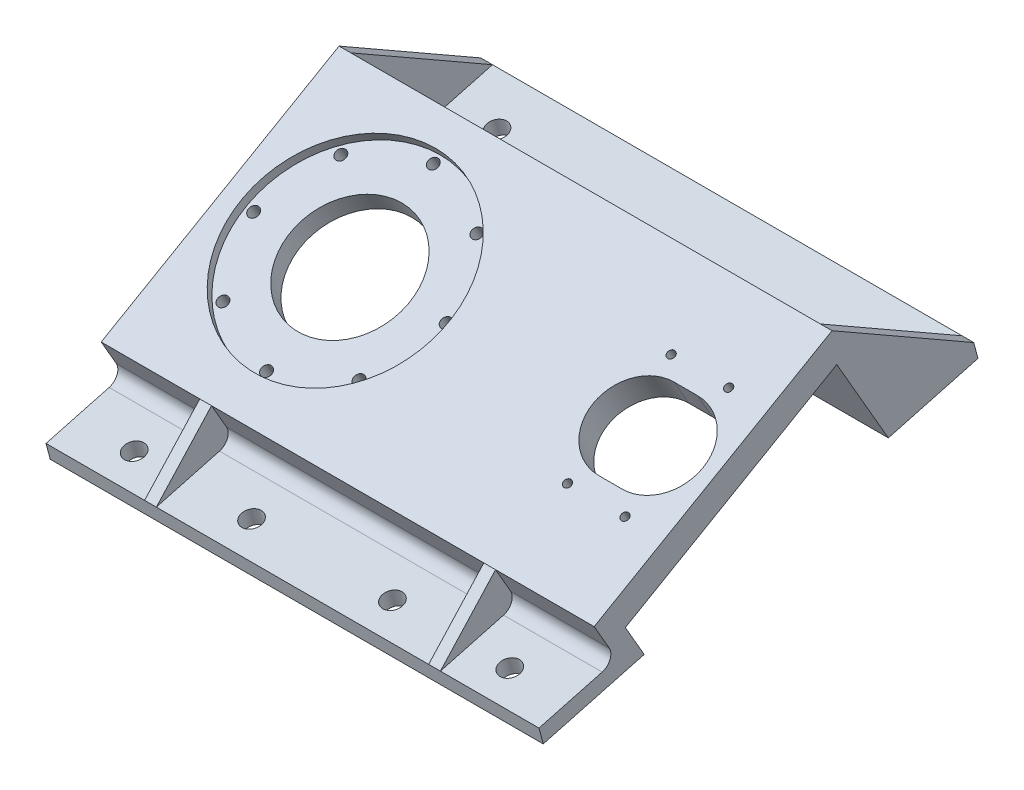
SolidWorks part; units mm, degrees
other "标注1"
sketch "草图25" plane through (-52, 30, -95) normal (-0.4172, 0.7166, -0.559) x (-0.8994, -0.2372, 0.3671)
other "标注2"
sketch "草图26" plane through (-52, 30, -95) normal (-0.4172, 0.7166, -0.559) x (-0.8994, -0.2372, 0.3671)
material "1060 合金"
ref_plane "前视基准面" through (0, 0, 0) normal (0, 0, 1) x (1, 0, 0)
ref_plane "上视基准面" through (0, 0, 0) normal (0, 1, 0) x (1, 0, 0)
ref_plane "右视基准面" through (0, 0, 0) normal (1, 0, 0) x (0, 0, -1)
sketch "草图1" plane through (0, 0, 0) normal (0, 1, 0) x (1, 0, 0)
  line L0 (0, 0) -> (170, 0) construction
  line L1 (170, 31.93) -> (170, -31.93)
  line L2 (15.8391, 73.3084) -> (162.1119, 41.7045)
  line L3 (15.8391, -73.3084) -> (162.1119, -41.7045)
  arc A0 (15.8391, 73.3084) -> (15.8391, -73.3084) centre (0, 0) ccw
  arc A1 (162.1119, -41.7045) -> (170, -31.93) centre (160, -31.93) ccw
  arc A2 (170, 31.93) -> (162.1119, 41.7045) centre (160, 31.93) ccw
  point P6 (170, 0)
  dimension "D1" = 150
  dimension "D4" = 20
  dimension "D5" = 20
  dimension "D2" = 170
  dimension "D3" = 63.86
extrude "凸台-拉伸1" add sketch "草图1" along normal blind 30
sketch "草图2" plane through (0, 30, 0) normal (0, 1, 0) x (1, 0, 0)
  circle A0 centre (0, 0) radius 44.45
  dimension "D1" = 88.9
extrude "切除-拉伸1" cut sketch "草图2" against normal blind 4
sketch "草图3" plane through (0, 26, 0) normal (0, 1, 0) x (1, 0, 0)
  line L0 (0, 0) -> (0, 90.3276) construction
  circle A0 centre (0, 0) radius 25.5
  circle A1 centre (0, 41) radius 2.25
  circle A2 centre (28.9914, 28.9914) radius 2.25
  circle A3 centre (41, 0) radius 2.25
  circle A4 centre (28.9914, -28.9914) radius 2.25
  circle A5 centre (0, -41) radius 2.25
  circle A6 centre (-28.9914, -28.9914) radius 2.25
  circle A7 centre (-41, 0) radius 2.25
  circle A8 centre (-28.9914, 28.9914) radius 2.25
  dimension "D1" = 51
  dimension "D3" = 4.5
  dimension "D2" = 41
  dimension "D4" = 8
extrude "切除-拉伸2" cut sketch "草图3" against normal through all contours A2 | A3 | A4 | A5 | A6 | A7 | A8 | A1 | A0
sketch "草图4" plane through (0, 30, 0) normal (0, 1, 0) x (1, 0, 0)
  line L0 (0, 0) -> (134, 0) construction
  line L1 (124, 18.5) -> (134, 18.5)
  line L2 (124, -18.5) -> (134, -18.5)
  arc A0 (134, -18.5) -> (134, 18.5) centre (134, 0) ccw
  arc A1 (124, 18.5) -> (124, -18.5) centre (124, 0) ccw
  dimension "D2" = 37
  dimension "D3" = 37
  dimension "D1" = 134
  dimension "D4" = 10
extrude "切除-拉伸3" cut sketch "草图4" against normal through all
sketch "草图5" plane through (0, 30, 0) normal (0, 1, 0) x (1, 0, 0)
  arc A0 (134, -18.5) -> (134, 18.5) centre (134, 0) ccw construction
  arc A1 (124, 18.5) -> (124, -18.5) centre (124, 0) ccw construction
  arc A2 (134, -18.5) -> (134, 18.5) centre (134, 0) ccw construction
  arc A3 (124, 18.5) -> (124, -18.5) centre (124, 0) ccw construction
  circle A4 centre (116.75, 25.5) radius 1.65
  circle A5 centre (141.25, 25.5) radius 1.65
  circle A6 centre (141.25, -25.5) radius 1.65
  circle A7 centre (116.75, -25.5) radius 1.65
  dimension "D1" = 3.3
  dimension "D2" = 3.3
  dimension "D3" = 3.3
  dimension "D4" = 3.3
  dimension "D7" = 25.5
  dimension "D5" = 7.25
  dimension "D6" = 25.5
  dimension "D8" = 7.25
  dimension "D9" = 7.25
extrude "切除-拉伸4" cut sketch "草图5" against normal through all
sketch "草图6" plane through (0, 30, 0) normal (0, 1, 0) x (1, 0, 0)
  line L0 (158, 42.5929) -> (158, -42.5929) construction
  line L2 (-52, 54.0463) -> (-52, -54.0463) construction
  line L6 (162.1119, 41.7045) -> (15.8391, 73.3084) construction
  line L7 (15.8391, -73.3084) -> (162.1119, -41.7045) construction
  line L8 (-52, 95) -> (-52, -95)
  line L9 (158, 95) -> (158, -95)
  line L10 (-52, 95) -> (158, 95)
  line L11 (-52, -95) -> (158, -95)
  line L15 (162.1119, 41.7045) -> (15.8391, 73.3084)
  line L16 (15.8391, -73.3084) -> (162.1119, -41.7045)
  line L17 (170, -31.93) -> (170, 31.93)
  line L18 (162.1119, 41.7045) -> (15.8391, 73.3084)
  line L19 (15.8391, -73.3084) -> (162.1119, -41.7045)
  line L20 (170, -31.93) -> (170, 31.93)
  arc A0 (15.8391, 73.3084) -> (15.8391, -73.3084) centre (0, 0) ccw construction
  arc A6 (170, 31.93) -> (162.1119, 41.7045) centre (160, 31.93) ccw
  arc A7 (15.8391, 73.3084) -> (15.8391, -73.3084) centre (0, 0) ccw
  arc A8 (162.1119, -41.7045) -> (170, -31.93) centre (160, -31.93) ccw
  arc A9 (170, 31.93) -> (162.1119, 41.7045) centre (160, 31.93) ccw
  arc A10 (15.8391, 73.3084) -> (15.8391, -73.3084) centre (0, 0) ccw
  arc A11 (162.1119, -41.7045) -> (170, -31.93) centre (160, -31.93) ccw
  point P8 (-52, 0)
  point P13 (158, 0)
  line M26 (162.1119, 41.7045) -> (15.8391, 73.3084)
  arc M27 (15.8391, 73.3084) -> (15.8391, -73.3084) centre (0, 0) ccw
  line M28 (15.8391, -73.3084) -> (162.1119, -41.7045)
  dimension "D3" = 190
  dimension "D1" = 210
  dimension "D2" = 52
  dimension "D4" = 190
  dimension "D5" = 0
extrude "凸台-拉伸2" add sketch "草图6" against normal blind 30 contours L10 L8 L9 M27 M26 | L8 L11 L9 M28 M27
sketch "草图7" plane through (0, 30, 0) normal (0, 1, 0) x (1, 0, 0)
  line L0 (-52, 54.0463) -> (-52, -54.0463)
  line L1 (158, 42.5929) -> (158, -42.5929)
  line L9 (162.1119, 41.7045) -> (158, 42.5929)
  line L10 (158, 42.5929) -> (158, 95)
  line L11 (158, 95) -> (-52, 95)
  line L12 (-52, 95) -> (-52, 54.0463)
  line L13 (-52, -54.0463) -> (-52, -95)
  line L14 (-52, -95) -> (158, -95)
  line L15 (158, -95) -> (158, -42.5929)
  line L16 (158, -42.5929) -> (162.1119, -41.7045)
  line L17 (170, -31.93) -> (170, 31.93)
  line L18 (162.1119, 41.7045) -> (158, 42.5929)
  line L21 (-52, 95) -> (-52, 54.0463)
  line L25 (158, -42.5929) -> (162.1119, -41.7045)
  line L26 (170, -31.93) -> (170, 31.93)
  arc A3 (170, 31.93) -> (162.1119, 41.7045) centre (160, 31.93) ccw
  arc A4 (-52, 54.0463) -> (-52, -54.0463) centre (0, 0) ccw
  arc A5 (162.1119, -41.7045) -> (170, -31.93) centre (160, -31.93) ccw
  arc A6 (170, 31.93) -> (162.1119, 41.7045) centre (160, 31.93) ccw
  arc A7 (-52, 54.0463) -> (-52, -54.0463) centre (0, 0) ccw
  arc A8 (162.1119, -41.7045) -> (170, -31.93) centre (160, -31.93) ccw
  arc M22 (170, 31.93) -> (162.1119, 41.7045) centre (160, 31.93) ccw
  line M23 (162.1119, 41.7045) -> (158, 42.5929)
  arc M27 (-52, 54.0463) -> (-52, -54.0463) centre (0, 0) ccw
  line M31 (158, -42.5929) -> (162.1119, -41.7045)
  arc M32 (162.1119, -41.7045) -> (170, -31.93) centre (160, -31.93) ccw
  line M33 (170, -31.93) -> (170, 31.93)
  dimension "D1" = 0
extrude "切除-拉伸5" cut sketch "草图7" against normal through all contours L0 M27 | L1 M23 M31 M32 M33 M22
sketch "草图9" plane through (-52, 0, 0) normal (-1, 0, 0) x (0, 0, 1)
  line L0 (-95, 20) -> (-60, 10.6218)
  line L1 (-95, 30) -> (95, 30) construction
  line L3 (-60, 10.6218) -> (-60, 30)
  line L5 (-95, 0) -> (-95, 30) construction
  line L7 (-95, 20) -> (-95, 30)
  line L8 (-95, 30) -> (-60, 30)
  dimension "D1" = 15
  dimension "D3" = 19.3782
  dimension "D4" = 35
  dimension "D5" = 10
extrude "切除-拉伸7" cut sketch "草图9" against normal through all contours L8 L3 L0 L7
sketch "草图8" plane through (-52, 0, 0) normal (-1, 0, 0) x (0, 0, 1)
  line L0 (0, 0) -> (52, 0)
  line L1 (-95, 0) -> (95, 0) construction
  line L2 (52, 0) -> (52, 17.3)
  line L3 (52, 17.3) -> (-52, 17.3)
  line L4 (-52, 17.3) -> (-52, 0)
  line L5 (-52, 0) -> (0, 0)
  line L6 (-60, 30) -> (95, 30) construction
  dimension "D1" = 52
  dimension "D2" = 52
  dimension "D3" = 12.7
sketch "草图10" plane through (-52, 0, 0) normal (-1, 0, 0) x (0, 0, 1)
  line L0 (-95, 12.7531) -> (-47.4049, 0) construction
  line L1 (-95, 0) -> (-95, 20) construction
  line L2 (-95, 0) -> (95, 0) construction
  line L3 (-95, 20) -> (-60, 10.6218) construction
  line L6 (-95, 12.7531) -> (-52, 1.2313)
  line L7 (-52, 1.2313) -> (-52, 0)
  line L8 (-95, 12.7531) -> (-95, 0)
  line L9 (-95, 0) -> (-52, 0)
  line L10 (-52, 17.3) -> (-52, 0) construction
  dimension "D1" = 7
extrude "切除-拉伸8" cut sketch "草图10" against normal through all
extrude "切除-拉伸9" cut sketch "草图8" against normal through all
fillet "圆角1" radius 5 1 edges at (53, 10.6218, -60)
sketch "草图11" plane through (-52, 0, 0) normal (-1, 0, 0) x (0, 0, 1)
  line L0 (-95, 12.7531) -> (-93.1883, 19.5145)
  line L1 (-95, 20) -> (-66.2941, 12.3083) construction
  line L2 (-93.1883, 19.5145) -> (-95, 20)
  line L3 (-95, 20) -> (-95, 12.7531)
extrude "切除-拉伸10" cut sketch "草图11" against normal through all
sketch "草图12" plane through (-52, 0, 0) normal (-1, 0, 0) x (0, 0, 1)
  line L0 (-93.1883, 19.5145) -> (-60, 30)
  line L10 (-93.1883, 19.5145) -> (-95, 12.7531)
  line L11 (-95, 12.7531) -> (-52, 1.2313)
  line L12 (-52, 1.2313) -> (-52, 17.3)
  line L13 (-52, 17.3) -> (52, 17.3)
  line L14 (52, 17.3) -> (52, 0)
  line L15 (52, 0) -> (95, 0)
  line L16 (95, 0) -> (95, 30)
  line L17 (95, 30) -> (-60, 30)
  line L18 (-60, 30) -> (-60, 17.1379)
  line L19 (-66.2941, 12.3083) -> (-93.1883, 19.5145)
  line L28 (-60, 30) -> (-60, 17.1379)
  line L29 (-66.2941, 12.3083) -> (-93.1883, 19.5145)
  arc A1 (-66.2941, 12.3083) -> (-60, 17.1379) centre (-65, 17.1379) ccw
  arc A2 (-66.2941, 12.3083) -> (-60, 17.1379) centre (-65, 17.1379) ccw
  dimension "D1" = 0
extrude "凸台-拉伸3" add sketch "草图12" against normal blind 5
sketch "草图13" plane through (158, 0, 0) normal (1, 0, 0) x (0, 0, -1)
  line L3 (66.2941, 12.3083) -> (93.1883, 19.5145)
  line L4 (93.1883, 19.5145) -> (60, 30)
  line L5 (60, 30) -> (60, 17.1379)
  line L6 (66.2941, 12.3083) -> (93.1883, 19.5145)
  line L7 (93.1883, 19.5145) -> (60, 30)
  line L8 (60, 30) -> (60, 17.1379)
  arc A1 (60, 17.1379) -> (66.2941, 12.3083) centre (65, 17.1379) ccw
  arc A2 (60, 17.1379) -> (66.2941, 12.3083) centre (65, 17.1379) ccw
  dimension "D1" = 0
extrude "凸台-拉伸4" add sketch "草图13" against normal blind 5
sketch "草图14" plane through (0, -5.0897, -1.3638) normal (0, 0.9659, 0.2588) x (1, 0, 0)
  line L0 (153, 67.2208) -> (153, 95.0637) construction
  line L3 (153, 95.0637) -> (-47, 95.0637) construction
  circle A0 centre (-27, 82.0637) radius 4.25
  circle A1 centre (23, 82.0637) radius 4.25
  circle A2 centre (83, 82.0637) radius 4.25
  circle A3 centre (133, 82.0637) radius 4.25
  dimension "D1" = 8.5
  dimension "D2" = 160
  dimension "D3" = 20
  dimension "D4" = 50
  dimension "D5" = 50
  dimension "D6" = 13
extrude "切除-拉伸11" cut sketch "草图14" against normal through all
sketch "草图16" plane through (-52, 0, 0) normal (-1, 0, 0) x (0, 0, 1)
  line L0 (-60, 30) -> (95, 30) construction
  line L1 (95, 0) -> (52, 0)
  line L2 (95, 0) -> (95, 30)
  line L3 (95, 30) -> (52, 30)
  line L4 (52, 0) -> (52, 30)
extrude "切除-拉伸12" cut sketch "草图16" against normal through all
ref_plane "基准面1" through (0, -11.8512, -3.1755) normal (0, -0.9659, -0.2588) x (-1, 0, 0)
sketch "草图18" plane through (0, 30, 0) normal (0, 1, 0) x (1, 0, 0)
  line L1 (-52, -52) -> (158, -52)
  line L2 (-52, -52) -> (-52, -57)
  line L3 (-52, -57) -> (158, -57)
  line L4 (158, -52) -> (158, -57)
  dimension "D1" = 5
extrude "凸台-拉伸7" add sketch "草图18" against normal up to surface (56.6355 mm away) up to plane "基准面1"
sketch "草图19" plane through (-52, 0, 0) normal (-1, 0, 0) x (0, 0, 1)
  line L0 (57, -27.9752) -> (90.1883, -36.868)
  line L1 (90.1883, -36.868) -> (92, -30.1065)
  line L2 (92, -30.1065) -> (57, -20.7283)
  line L3 (57, -27.9752) -> (57, 30) construction
  line L4 (57, -20.7283) -> (57, -27.9752)
  line L5 (52, -26.6355) -> (57, -27.9752) construction
  dimension "D1" = 7
  dimension "D2" = 40
extrude "凸台-拉伸8" add sketch "草图19" against normal up to surface (210 mm away) up to face at (158, 8.1654, -14.9098)
sketch "草图20" plane through (-52, 0, 0) normal (-1, 0, 0) x (0, 0, 1)
  line L0 (92, -30.1065) -> (57, -20.7283) construction
  line L1 (57, -20.7283) -> (57, 30) construction
  line L2 (92, -30.1065) -> (57, -20.7283)
  line L3 (57, -20.7283) -> (57, 30)
  line L4 (57, 30) -> (92, -30.1065)
extrude "凸台-拉伸9" add sketch "草图20" against normal blind 5
sketch "草图21" plane through (158, 0, 0) normal (1, 0, 0) x (0, 0, -1)
  line L3 (-57, 30) -> (-92, -30.1065)
  line L4 (-92, -30.1065) -> (-57, -20.7283)
  line L5 (-57, -20.7283) -> (-57, 30)
  line L6 (-57, 30) -> (-92, -30.1065)
  line L7 (-92, -30.1065) -> (-57, -20.7283)
  line L8 (-57, -20.7283) -> (-57, 30)
  dimension "D1" = 0
extrude "凸台-拉伸10" add sketch "草图21" against normal blind 5
sketch "草图22" plane through (0, -5.0897, -1.3638) normal (0, 0.9659, 0.2588) x (1, 0, 0)
  line L0 (-47, -96.6573) -> (-47, -47.2932) construction
  line L2 (153, -96.6573) -> (153, -60.4226) construction
  circle A0 centre (-27, -77.9363) radius 4.25
  circle A1 centre (23, -69.9363) radius 4.25
  circle A2 centre (83, -69.9363) radius 4.25
  circle A3 centre (133, -77.9363) radius 4.25
  circle A4 centre (133, 82.0637) radius 4.25 construction
  circle A5 centre (-27, 82.0637) radius 4.25 construction
  circle A6 centre (23, 82.0637) radius 4.25 construction
  circle A7 centre (83, 82.0637) radius 4.25 construction
  dimension "D1" = 8.5
  dimension "D7" = 152
  dimension "D6" = 152
  dimension "D8" = 50
  dimension "D4" = 160
  dimension "D5" = 160
  dimension "D2" = 20
  dimension "D3" = 20
  dimension "D9" = 50
extrude "切除-拉伸13" cut sketch "草图22" against normal through all
fillet "圆角2" radius 5 1 edges at (53, -20.7283, 57)
ref_plane "基准面2" through (113.5, 0, 0) normal (1, 0, 0) x (0, 0, -1)
sketch "草图27" plane through (113.5, 0, 0) normal (1, 0, 0) x (0, 0, -1)
  line L3 (60, 30) -> (60, 17.1379)
  line L4 (93.1883, 19.5145) -> (60, 30)
  line L5 (66.2941, 12.3083) -> (93.1883, 19.5145)
  line L6 (60, 30) -> (60, 17.1379)
  line L7 (93.1883, 19.5145) -> (60, 30)
  line L8 (66.2941, 12.3083) -> (93.1883, 19.5145)
  arc A1 (60, 17.1379) -> (66.2941, 12.3083) centre (65, 17.1379) ccw
  arc A2 (60, 17.1379) -> (66.2941, 12.3083) centre (65, 17.1379) ccw
  dimension "D1" = 0
extrude "凸台-拉伸11" add sketch "草图27" along normal mid plane 5
sketch "草图29" plane through (153, 0, 0) normal (-1, 0, 0) x (0, 0, 1)
  line L3 (-60, 17.1379) -> (-60, 30)
  line L4 (-60, 30) -> (-93.1883, 19.5145)
  line L5 (-93.1883, 19.5145) -> (-66.2941, 12.3083)
  line L6 (-60, 17.1379) -> (-60, 30)
  line L7 (-60, 30) -> (-93.1883, 19.5145)
  line L8 (-93.1883, 19.5145) -> (-66.2941, 12.3083)
  arc A1 (-66.2941, 12.3083) -> (-60, 17.1379) centre (-65, 17.1379) ccw
  arc A2 (-66.2941, 12.3083) -> (-60, 17.1379) centre (-65, 17.1379) ccw
  dimension "D1" = 0
extrude "切除-拉伸16" cut sketch "草图29" against normal blind 5
ref_plane "基准面3" through (-7.5, 0, 0) normal (-1, 0, 0) x (0, 0, 1)
sketch "草图30" plane through (-7.5, 0, 0) normal (-1, 0, 0) x (0, 0, 1)
  line L5 (-93.1883, 19.5145) -> (-66.2941, 12.3083)
  line L6 (-60, 30) -> (-93.1883, 19.5145)
  line L7 (-60, 17.1379) -> (-60, 30)
  line L10 (-93.1883, 19.5145) -> (-66.2941, 12.3083)
  line L11 (-60, 30) -> (-93.1883, 19.5145)
  line L12 (-60, 17.1379) -> (-60, 30)
  arc A1 (-66.2941, 12.3083) -> (-60, 17.1379) centre (-65, 17.1379) ccw
  arc A2 (-66.2941, 12.3083) -> (-60, 17.1379) centre (-65, 17.1379) ccw
  dimension "D1" = 0
extrude "凸台-拉伸12" add sketch "草图30" along normal mid plane 5
sketch "草图31" plane through (-47, 0, 0) normal (1, 0, 0) x (0, 0, -1)
  line L5 (66.2941, 12.3083) -> (93.1883, 19.5145)
  line L6 (93.1883, 19.5145) -> (60, 30)
  line L7 (60, 30) -> (60, 17.1379)
  line L10 (66.2941, 12.3083) -> (93.1883, 19.5145)
  line L11 (93.1883, 19.5145) -> (60, 30)
  line L12 (60, 30) -> (60, 17.1379)
  arc A1 (60, 17.1379) -> (66.2941, 12.3083) centre (65, 17.1379) ccw
  arc A2 (60, 17.1379) -> (66.2941, 12.3083) centre (65, 17.1379) ccw
  dimension "D1" = 0
extrude "切除-拉伸18" cut sketch "草图31" against normal blind 5
mirror "镜向2" about plane through (158, 12.7531, -95) normal (0, -0.2588, 0.9659) of bodies 137
sketch "草图32" plane through (-52, 0, 0) normal (-1, 0, 0) x (0, 0, 1)
  line L0 (-93.1883, 19.5145) -> (-95, 12.7531) construction
  line L1 (-52, 1.2313) -> (-138, 24.2749) construction
  line L2 (-93.1883, 19.5145) -> (-80.5062, 66.8447)
  line L3 (-80.5062, 66.8447) -> (104.6821, 17.2236)
  line L4 (-95, 12.7531) -> (90.1883, -36.868)
  line L5 (52, -26.6355) -> (90.1883, -36.868) construction
  line L6 (104.6821, 17.2236) -> (90.1883, -36.868)
  line L7 (-93.1883, 19.5145) -> (-95, 12.7531)
extrude "切除-拉伸19" cut sketch "草图32" against normal through all
